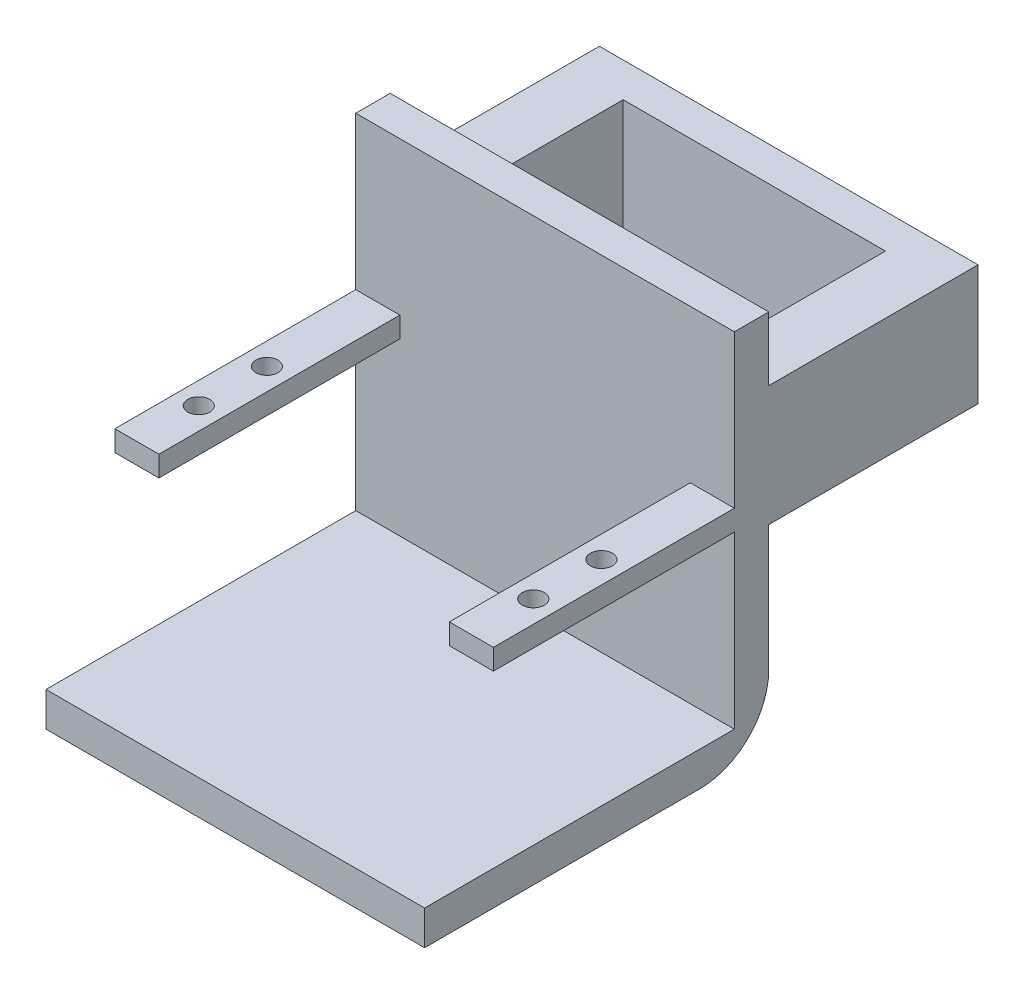
SolidWorks part; units mm, degrees
material "ABS"
ref_plane "Front Plane" through (0, 0, 0) normal (0, 0, 1) x (1, 0, 0)
ref_plane "Top Plane" through (0, 0, 0) normal (0, 1, 0) x (1, 0, 0)
ref_plane "Right Plane" through (0, 0, 0) normal (1, 0, 0) x (0, 0, -1)
sketch "Sketch1" plane through (0, 0, 0) normal (0, 0, 1) x (1, 0, 0)
  line L1 (-20.414, 27.8981) -> (34.586, 27.8981)
  line L2 (-20.414, 27.8981) -> (-20.414, -27.1019)
  line L3 (-20.414, -27.1019) -> (34.586, -27.1019)
  line L4 (34.586, 27.8981) -> (34.586, -27.1019)
  dimension "D1" = 55
  dimension "D2" = 55
extrude "Boss-Extrude1" add sketch "Sketch1" along normal blind 50
sketch "Sketch2" plane through (0, 0, 50) normal (0, 0, 1) x (1, 0, 0)
  line L0 (34.586, -27.1019) -> (34.586, 27.8981) construction
  line L1 (-20.414, 27.8981) -> (34.586, 27.8981)
  line L2 (-20.414, 27.8981) -> (-20.414, -22.1019)
  line L3 (-20.414, -22.1019) -> (34.586, -22.1019)
  line L4 (34.586, 27.8981) -> (34.586, -22.1019)
  dimension "D1" = 50
extrude "Cut-Extrude1" cut sketch "Sketch2" against normal blind 45
fillet "Fillet2" radius 10 1 edges at (7.086, -27.1019, 0)
sketch "Sketch3" plane through (0, 0, 5) normal (0, 0, 1) x (1, 0, 0)
  line L0 (-14.014, 5.6981) -> (-14.014, 2.6981)
  line L2 (34.586, 5.6981) -> (28.186, 5.6981)
  line L3 (34.586, -22.1019) -> (34.586, 27.8981) construction
  line L4 (28.186, 5.6981) -> (28.186, 2.6981)
  line L5 (-20.414, 5.6981) -> (-14.014, 5.6981)
  line L6 (-20.414, 27.8981) -> (-20.414, -22.1019) construction
  line L7 (-14.014, 2.6981) -> (-20.414, 2.6981)
  line L8 (-20.414, 2.6981) -> (-20.414, 5.6981)
  line L9 (28.186, 2.6981) -> (34.586, 2.6981)
  line L10 (34.586, 2.6981) -> (34.586, 5.6981)
extrude "Boss-Extrude2" add sketch "Sketch3" along normal blind 35
sketch "Sketch4" plane through (0, 5.6981, 0) normal (0, 1, 0) x (1, 0, 0)
  circle A0 centre (-17.214, -21.11) radius 1.6
  circle A1 centre (-17.214, -31.01) radius 1.6
  circle A2 centre (31.386, -31.01) radius 1.6
  circle A3 centre (31.386, -21.11) radius 1.6
  dimension "D1" = 3.2
  dimension "D2" = 3.2
  dimension "D4" = 3.2
  dimension "D3" = 3.2
extrude "Cut-Extrude2" cut sketch "Sketch4" against normal blind 10
sketch "Sketch5" plane through (0, 0, 0) normal (0, 0, -1) x (-1, 0, 0)
  line L0 (-7.086, 27.8981) -> (-7.086, -17.1019) construction
  line L1 (-34.586, 27.8981) -> (20.414, 27.8981) construction
  line L2 (-34.586, -17.1019) -> (20.414, -17.1019) construction
  line L3 (-7.086, 18.622) -> (11.964, 18.622) construction
  line L4 (-7.086, 18.622) -> (-26.136, 18.622) construction
  line L5 (-34.586, -17.1019) -> (-34.586, 27.8981) construction
  line L6 (-26.136, 18.622) -> (-34.586, 18.622)
  line L7 (-26.136, 18.622) -> (-26.136, 1.1349)
  line L8 (-26.136, 1.1349) -> (-34.586, 1.1349)
  line L9 (-34.586, 18.622) -> (-34.586, 1.1349)
  line L10 (20.414, 27.8981) -> (20.414, -17.1019) construction
  line L11 (11.964, 18.622) -> (20.414, 18.622)
  line L12 (11.964, 18.622) -> (11.964, 1.1349)
  line L13 (11.964, 1.1349) -> (20.414, 1.1349)
  line L14 (20.414, 18.622) -> (20.414, 1.1349)
extrude "Boss-Extrude3" add sketch "Sketch5" along normal blind 25.4
sketch "Sketch6" plane through (0, 0, -25.4) normal (0, 0, -1) x (-1, 0, 0)
  line L1 (-34.586, 1.1349) -> (20.414, 1.1349)
  line L2 (-34.586, 1.1349) -> (-34.586, 18.622)
  line L3 (-34.586, 18.622) -> (20.414, 18.622)
  line L4 (20.414, 1.1349) -> (20.414, 18.622)
extrude "Boss-Extrude4" add sketch "Sketch6" along normal blind 5
